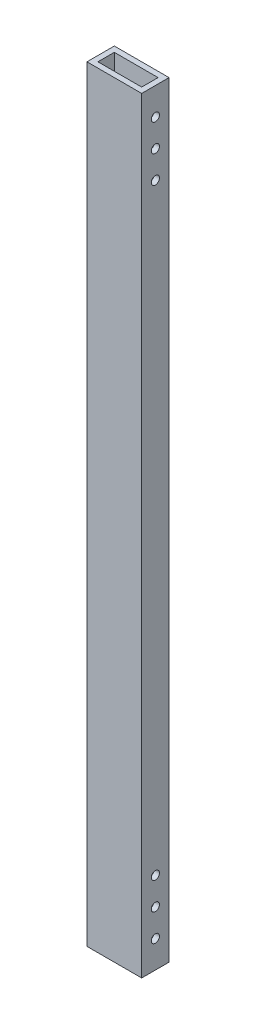
SolidWorks part; units mm, degrees
ref_plane "前视基准面" through (0, 0, 0) normal (0, 0, 1) x (1, 0, 0)
ref_plane "上视基准面" through (0, 0, 0) normal (0, 1, 0) x (1, 0, 0)
ref_plane "右视基准面" through (0, 0, 0) normal (1, 0, 0) x (0, 0, -1)
sketch "草图1" plane through (0, 0, 0) normal (0, 1, 0) x (1, 0, 0)
  line L1 (-10, 5) -> (10, 5)
  line L2 (-10, 5) -> (-10, -5)
  line L3 (-10, -5) -> (10, -5)
  line L4 (10, 5) -> (10, -5)
  line L5 (-10, 5) -> (10, -5) construction
  line L6 (-10, -5) -> (10, 5) construction
  line L7 (-8, 3) -> (8, 3)
  line L8 (-8, 3) -> (-8, -3)
  line L9 (-8, -3) -> (8, -3)
  line L10 (8, 3) -> (8, -3)
  line L11 (-8, 3) -> (8, -3) construction
  line L12 (-8, -3) -> (8, 3) construction
  point P0 (0, 0)
  point P6 (0, 0)
  dimension "D1" = 10
  dimension "D2" = 20
  dimension "D3" = 2
  dimension "D4" = 2
extrude "凸台-拉伸1" add sketch "草图1" along normal mid plane 280
sketch "草图3" plane through (10, 0, 0) normal (1, 0, 0) x (0, 0, -1)
  line L0 (0, 110) -> (0, 130) construction
  line L1 (-5, 140) -> (5, 140) construction
  line L2 (0, 0) -> (20.3275, 0) construction
  circle A0 centre (0, 130) radius 1.5
  circle A1 centre (0, 120) radius 1.5
  circle A2 centre (0, 110) radius 1.5
  circle A3 centre (0, -110) radius 1.5
  circle A4 centre (0, -120) radius 1.5
  circle A5 centre (0, -130) radius 1.5
  dimension "D4" = 3
  dimension "D1" = 10
  dimension "D2" = 10
  dimension "D3" = 10
extrude "切除-拉伸1" cut sketch "草图3" against normal through all
